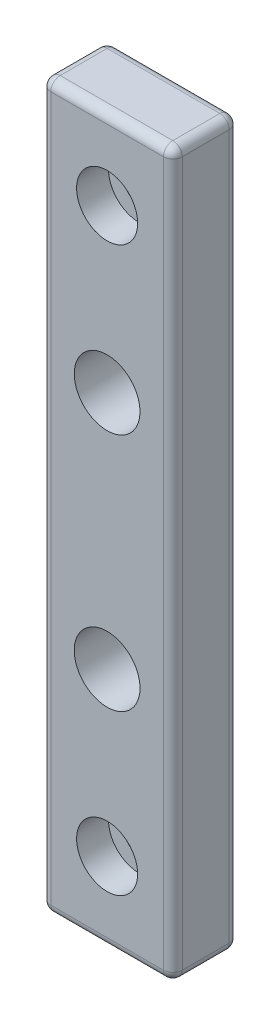
SolidWorks part; units mm, degrees
ref_plane "Top Plane" through (0, 0, 0) normal (0, 0, 1) x (1, 0, 0)
ref_plane "Right Plane" through (0, 0, 0) normal (0, 1, 0) x (1, 0, 0)
ref_plane "Front Plane" through (0, 0, 0) normal (1, 0, 0) x (0, 0, -1)
sketch "Sketch1" plane through (0, 0, 0) normal (0, 0, 1) x (1, 0, 0)
  line L0 (-7, 38.5) -> (7, -38.5) construction
  line L1 (-7, 38.5) -> (7, 38.5)
  line L2 (-7, 38.5) -> (-7, -38.5)
  line L3 (-7, -38.5) -> (7, -38.5)
  line L4 (7, 38.5) -> (7, -38.5)
  line L5 (-16.3874, 0) -> (22.1614, 0) construction
  circle A0 centre (0, 30) radius 1.5 construction
  circle A1 centre (0, -30) radius 1.5 construction
  circle A2 centre (0, -12.75) radius 2.5 construction
  circle A3 centre (0, 12.75) radius 2.5 construction
  point P15 (0, 0)
  dimension "D3" = 60
  dimension "D4" = 3
  dimension "D5" = 25.5
  dimension "D6" = 5
  dimension "D1" = 14
  dimension "D2" = 77
extrude "Boss-Extrude1" add sketch "Sketch1" along normal mid plane 7
hole_wizard "CBORE for M3 Hex Socket Head Cap Screw1" positions "Sketch2" profile "Sketch3" counterbore size "M3" standard "ISO" end condition through all
sketch "Sketch2" plane through (0, 0, 3.5) normal (0, 0, 1) x (1, 0, 0)
  point P0 (0, -30)
  point P3 (0, 30)
sketch "Sketch3" plane through (0, -30, 3.5) normal (1, 0, 0) x (0, -1, 0)
  line L0 (0, 0) -> (0, 7)
  line L1 (0, 7) -> (1.6, 7)
  line L3 (1.6, 7) -> (1.6, 3.4)
  line L4 (1.6, 3.4) -> (3.25, 3.4)
  line L5 (3.25, 3.4) -> (3.25, 0)
  line L7 (3.25, 0) -> (0, 0)
  line L11 (0, -6.35) -> (0, 107.95) construction
  dimension "Thru Hole Dia." = 3.2
  dimension "Thru Hole Depth" = 7
  dimension "C'Bore Dia." = 6.5
  dimension "C'Bore Depth" = 3.4
sketch "Sketch4" plane through (0, 0, 3.5) normal (0, 0, 1) x (1, 0, 0)
  line L0 (-16.3874, 0) -> (22.1614, 0) construction
  line L1 (-16.3874, 0) -> (22.1614, 0) construction
  circle A0 centre (0, -12.75) radius 3.5
  circle A1 centre (0, 12.75) radius 3.5
  dimension "D1" = 7
extrude "Cut-Extrude1" cut sketch "Sketch4" against normal through all
fillet "Fillet1" radius 1 4 edges at (-7, 38.5, 0) (-7, -38.5, 0) (7, -38.5, 0) (7, 38.5, 0)
fillet "Fillet2" radius 1 16 edges at (6.7071, -38.2071, 3.5) (0, -38.5, 3.5) (-6.7071, -38.2071, 3.5) (-7, 0, 3.5) (-6.7071, 38.2071, 3.5) (0, 38.5, 3.5) (6.7071, 38.2071, 3.5) (6.7071, -38.2071, -3.5) (0, -38.5, -3.5) (-6.7071, -38.2071, -3.5) (-7, 0, -3.5) (-6.7071, 38.2071, -3.5) (0, 38.5, -3.5) (6.7071, 38.2071, -3.5) (7, 0, 3.5) (7, 0, -3.5)
